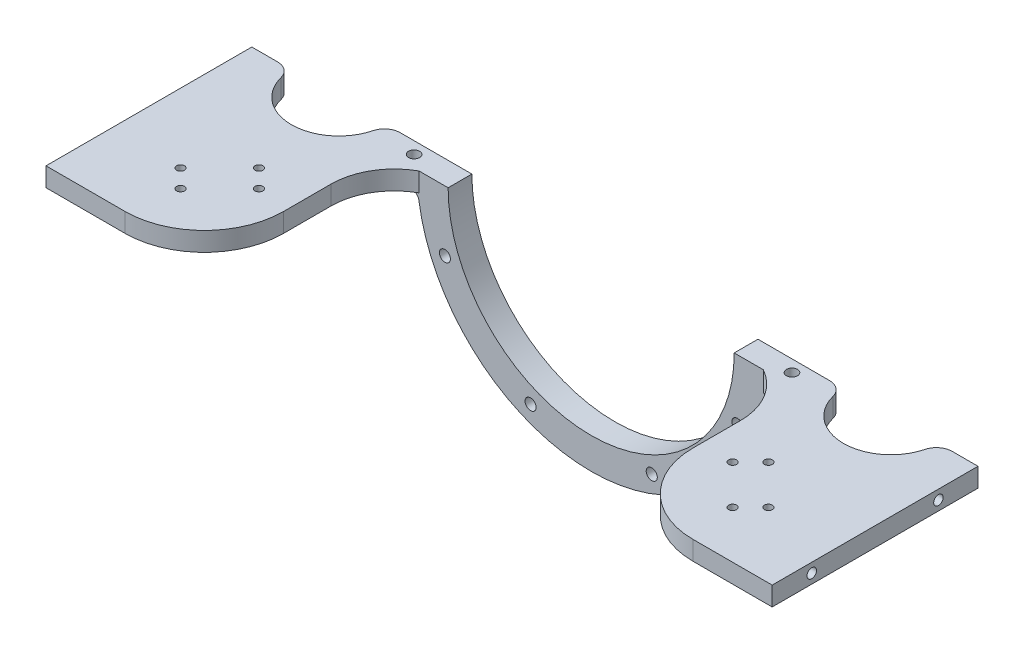
SolidWorks part; units mm, degrees
ref_plane "前视基准面" through (0, 0, 0) normal (0, 0, 1) x (1, 0, 0)
ref_plane "上视基准面" through (0, 0, 0) normal (0, 1, 0) x (1, 0, 0)
ref_plane "右视基准面" through (0, 0, 0) normal (1, 0, 0) x (0, 0, -1)
sketch "草图1" plane through (0, 0, 0) normal (0, 0, 1) x (1, 0, 0)
  line L0 (-122.8231, 0) -> (143.6792, 0) construction
  line L1 (38.2683, -92.388) -> (0, 0) construction
  line L2 (0, 0) -> (0, -120.3915) construction
  line L3 (-110, 0) -> (-90.35, 0)
  line L4 (90.35, 0) -> (110, 0)
  arc A0 (-90.35, 0) -> (90.35, 0) centre (0, 0) ccw
  arc A1 (-110, 0) -> (110, 0) centre (0, 0) ccw
  arc A2 (-100, 0) -> (100, 0) centre (0, 0) ccw construction
  circle A3 centre (38.2683, -92.388) radius 3.5
  circle A4 centre (-38.2683, -92.388) radius 3.5
  circle A5 centre (-92.388, -38.2683) radius 3.5
  circle A6 centre (-92.388, 38.2683) radius 3.5 [skipped]
  circle A7 centre (-38.2683, 92.388) radius 3.5 [skipped]
  circle A8 centre (38.2683, 92.388) radius 3.5 [skipped]
  circle A9 centre (92.388, 38.2683) radius 3.5 [skipped]
  circle A10 centre (92.388, -38.2683) radius 3.5
  point P30 (0, 0)
  dimension "D1" = 22.5
  dimension "D3" = 7
  dimension "D4" = 100
  dimension "D5" = 110
  dimension "D6" = 90.35
  dimension "D2" = 8
extrude "凸台-拉伸1" add sketch "草图1" along normal blind 15
sketch "草图2" plane through (0, 0, 15) normal (0, 0, 1) x (1, 0, 0)
  line L0 (-110, 0) -> (-129.3435, 0)
  line L1 (-129.3435, 0) -> (-129.3435, -12)
  line L2 (-129.3435, -12) -> (-109.3435, -12)
  arc A0 (-110, 0) -> (110, 0) centre (0, 0) ccw construction
  arc A1 (-110, 0) -> (-109.3435, -12) centre (0, 0) ccw
  dimension "D1" = 12
  dimension "D2" = 20
extrude "凸台-拉伸2" add sketch "草图2" against normal up to surface (15 mm away) up to face at (0, -50.0875, 0)
sketch "草图3" plane through (0, -12, 0) normal (0, -1, 0) x (1, 0, 0)
  line L0 (-129.3435, 15) -> (-109.3435, 15) construction
  line L1 (-129.3435, 0) -> (-129.3435, 15) construction
  circle A0 centre (-119.3435, 7.5) radius 3.5
  dimension "D1" = 7
  dimension "D2" = 7.5
  dimension "D3" = 10
extrude "切除-拉伸1" cut sketch "草图3" against normal up to next
mirror "镜向1" about plane through (0, 0, 0) normal (1, 0, 0) of "切除-拉伸1", "凸台-拉伸2"
sketch "草图4" plane through (0, 0, 0) normal (0, 1, 0) x (1, 0, 0)
  line L0 (-129.3435, 0) -> (-229.3435, 0)
  line L1 (-229.3435, 0) -> (-229.3435, -130)
  line L2 (-229.3435, -130) -> (-129.3435, -130)
  line L3 (-129.3435, -130) -> (-129.3435, -50)
  line L5 (-129.3435, 0) -> (-129.3435, -15)
  line L7 (-90.35, -15) -> (-129.3435, -15) construction
  line L8 (-129.3435, -15) -> (-108.7084, -15)
  arc A0 (-129.3435, -50) -> (-108.7084, -15) centre (-89.3435, -50) cw
  dimension "D4" = 40
  dimension "D1" = 100
  dimension "D2" = 130
  dimension "D3" = 80
extrude "凸台-拉伸3" add sketch "草图4" against normal up to surface (12 mm away) up to face at (-115.8435, -12, 7.5)
sketch "草图7" plane through (0, 0, 0) normal (0, 1, 0) x (1, 0, 0)
  line L0 (-160.9085, -63.9376) -> (-149.5948, -75.2513) construction
  line L5 (-149.5948, -75.2513) -> (-174.3435, -100) construction
  line L6 (-174.3435, -100) -> (-185.6572, -88.6863) construction
  line L7 (-185.6572, -88.6863) -> (-160.9085, -63.9376) construction
  line L8 (-229.3435, -130) -> (-129.3435, -130) construction
  line L9 (-229.3435, 0) -> (-229.3435, -130) construction
  circle A0 centre (-185.6572, -88.6863) radius 2.5
  circle A1 centre (-174.3435, -100) radius 2.5
  circle A2 centre (-160.9085, -63.9376) radius 2.5
  circle A3 centre (-149.5948, -75.2513) radius 2.5
  dimension "D6" = 5
  dimension "D1" = 45
  dimension "D2" = 35
  dimension "D3" = 16
  dimension "D4" = 30
  dimension "D5" = 55
extrude "切除-拉伸2" cut sketch "草图7" against normal up to next
mirror "镜向2" about plane through (0, 0, 0) normal (1, 0, 0) of "切除-拉伸2", "凸台-拉伸3"
sketch "草图8" plane through (-229.3435, 0, 0) normal (-1, 0, 0) x (0, 0, 1)
  line L0 (0, -12) -> (0, 0) construction
  line L1 (130, -12) -> (130, 0) construction
  line L2 (0, 0) -> (130, 0) construction
  circle A0 centre (25, -6) radius 3
  circle A1 centre (105, -6) radius 3
  dimension "D1" = 6
  dimension "D2" = 6
  dimension "D3" = 25
  dimension "D4" = 25
  dimension "D5" = 6
  dimension "D6" = 6
extrude "切除-拉伸3" cut sketch "草图8" against normal blind 30
ref_plane "基准面1" through (-209.3435, 0, 0) normal (-1, 0, 0) x (0, 0, 1)
sketch "草图9" plane through (-209.3435, 0, 0) normal (-1, 0, 0) x (0, 0, 1)
  line L0 (20.75, -8.0859) -> (20.75, -12)
  line L1 (20.75, -3.5463) -> (20.75, -8.0859)
  line L4 (29.25, -8.2637) -> (29.25, -3.5463)
  line L5 (29.25, -3.5463) -> (25, -1.0925)
  line L6 (25, -1.0925) -> (20.75, -3.5463)
  line L7 (0, -12) -> (130, -12) construction
  line L9 (109.25, -3.5463) -> (105, -1.0925)
  line L10 (105, -1.0925) -> (100.75, -3.5463)
  line L11 (100.75, -3.5463) -> (100.75, -8.0859)
  line L14 (109.25, -8.2637) -> (109.25, -3.5463)
  line L15 (29.25, -12) -> (29.25, -8.2637)
  line L16 (20.75, -12) -> (29.25, -12)
  line L17 (22.875, -9.6806) -> (24.925, -10.8642) [skipped]
  line L18 (27.125, -9.6806) -> (29.175, -8.497) [skipped]
  line L19 (100.75, -8.0859) -> (100.75, -12)
  line L20 (100.75, -12) -> (109.25, -12)
  line L21 (109.25, -12) -> (109.25, -8.2637)
  line L23 (102.875, -9.6806) -> (104.925, -10.8642) [skipped]
  line L24 (107.125, -9.6806) -> (109.175, -8.497) [skipped]
  arc A4 (29.25, -6) -> (20.75, -6) centre (25, -6) ccw construction
  arc A5 (109.25, -6) -> (100.75, -6) centre (105, -6) ccw construction
  dimension "D1" = 8.5
  dimension "D2" = 8.5
extrude "切除-拉伸4" cut sketch "草图9" along normal blind 4.5
fillet "圆角1" radius 5 1 edges at (-109.3435, -12, 7.5)
fillet "圆角4" radius 5 1 edges at (109.3435, -12, 7.5)
mirror "镜向4" about plane through (0, 0, 0) normal (1, 0, 0) of "切除-拉伸4", "切除-拉伸3"
fillet "圆角5" radius 50 1 edges at (-129.3435, -6, 130)
fillet "圆角6" radius 50 1 edges at (129.3435, -6, 130)
sketch "草图10" plane through (0, 0, 0) normal (0, 1, 0) x (1, 0, 0)
  line L0 (-90.35, 0) -> (-229.3435, 0) construction
  line L1 (-204.3435, 0) -> (-144.3435, 0)
  line L2 (-229.3435, 0) -> (-229.3435, -130) construction
  arc A0 (-204.3435, 0) -> (-144.3435, 0) centre (-174.3435, 0) ccw
  dimension "D1" = 55
  dimension "D2" = 60
extrude "切除-拉伸5" cut sketch "草图10" against normal up to next
fillet "圆角7" radius 10 1 edges at (-204.3435, -6, 0)
fillet "圆角8" radius 10 1 edges at (-144.3435, -6, 0)
mirror "镜向8" about plane through (0, 0, 0) normal (1, 0, 0) of "切除-拉伸5"
fillet "圆角9" radius 10 1 edges at (204.3435, -6, 0)
fillet "圆角10" radius 10 1 edges at (144.3435, -6, 0)
